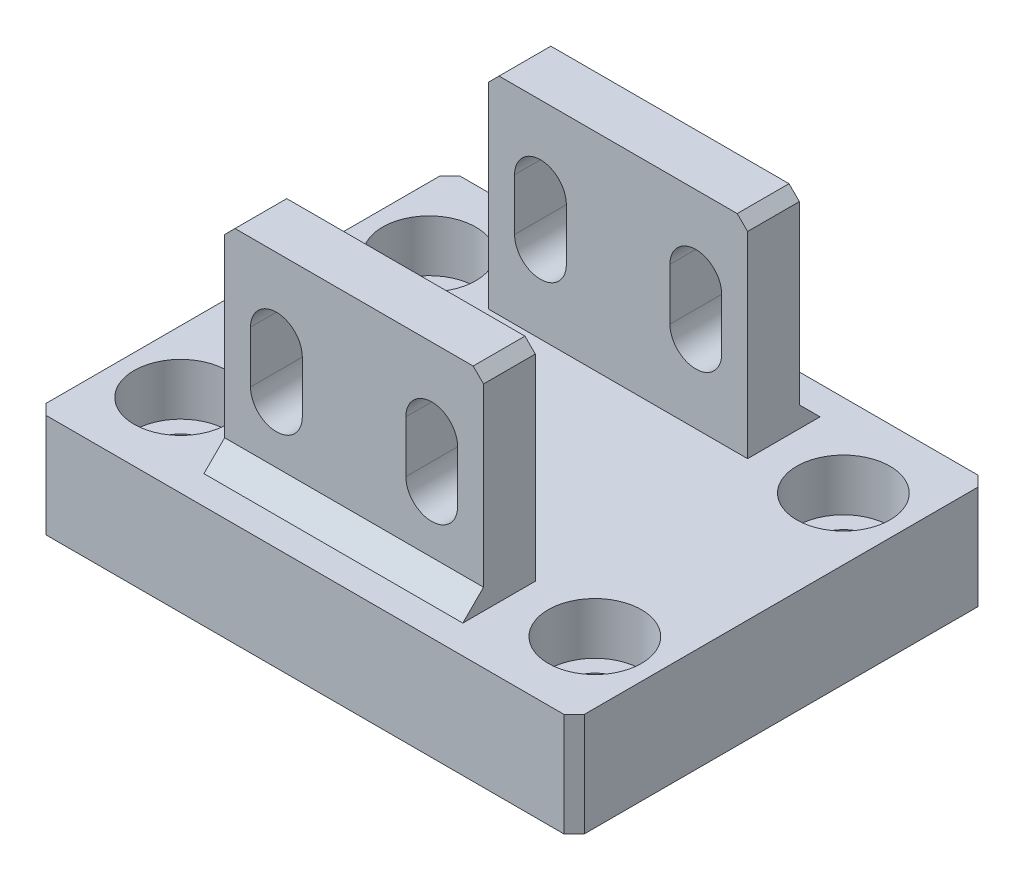
SolidWorks part; units mm, degrees
ref_plane "Front Plane" through (0, 0, 0) normal (0, 0, 1) x (1, 0, 0)
ref_plane "Top Plane" through (0, 0, 0) normal (0, 1, 0) x (1, 0, 0)
ref_plane "Right Plane" through (0, 0, 0) normal (1, 0, 0) x (0, 0, -1)
sketch "Sketch1" plane through (0, 0, 0) normal (0, 1, 0) x (1, 0, 0)
  line L1 (-26, 20) -> (26, 20)
  line L2 (-26, 20) -> (-26, -20)
  line L3 (-26, -20) -> (26, -20)
  line L4 (26, 20) -> (26, -20)
  line L5 (-26, 20) -> (26, -20) construction
  line L6 (-26, -20) -> (26, 20) construction
  line L7 (-20, 12) -> (20, 12) construction
  line L8 (-20, 12) -> (-20, -12) construction
  line L9 (-20, -12) -> (20, -12) construction
  line L10 (20, 12) -> (20, -12) construction
  line L11 (-20, 12) -> (20, -12) construction
  line L12 (-20, -12) -> (20, 12) construction
  circle A0 centre (-20, 12) radius 2.75
  circle A1 centre (20, 12) radius 2.75
  circle A2 centre (20, -12) radius 2.75
  circle A3 centre (-20, -12) radius 2.75
  point P0 (0, 0)
  point P6 (0, 0)
  dimension "D5" = 5.5
  dimension "D1" = 52
  dimension "D2" = 40
  dimension "D3" = 24
  dimension "D4" = 40
extrude "Boss-Extrude1" add sketch "Sketch1" along normal blind 10
sketch "Sketch4" plane through (0, 10, 0) normal (0, 1, 0) x (1, 0, 0)
  circle A0 centre (-20, 12) radius 4.5
  circle A1 centre (20, 12) radius 4.5
  circle A2 centre (20, -12) radius 4.5
  circle A3 centre (-20, -12) radius 4.5
  dimension "D1" = 9
extrude "Cut-Extrude2" cut sketch "Sketch4" against normal blind 5
sketch "Sketch2" plane through (26, 0, 0) normal (1, 0, 0) x (0, 0, -1)
  line L5 (0, -3.5148) -> (0, 6.6641) construction
  line L10 (-20, 10) -> (20, 10) construction
  line L11 (-15.25, 10) -> (-10.25, 10)
  line L12 (-15.25, 10) -> (-15.25, 30)
  line L13 (-15.25, 30) -> (-10.25, 30)
  line L14 (-10.25, 10) -> (-10.25, 30)
  line L16 (15.25, 10) -> (10.25, 10)
  line L17 (15.25, 10) -> (15.25, 30)
  line L18 (15.25, 30) -> (10.25, 30)
  line L19 (10.25, 10) -> (10.25, 30)
  dimension "D1" = 20.5
  dimension "D2" = 5
  dimension "D3" = 20
extrude "Boss-Extrude2" add sketch "Sketch2" against normal blind 25 from offset 13.5 offset against normal yes
sketch "Sketch3" plane through (0, 0, 15.25) normal (0, 0, 1) x (1, 0, 0)
  line L0 (-7.5, 22.5) -> (-7.5, 17.5) construction
  line L1 (-5, 22.5) -> (-5, 17.5)
  line L2 (-10, 22.5) -> (-10, 17.5)
  line L3 (7.5, 22.5) -> (7.5, 17.5) construction
  line L4 (10, 22.5) -> (10, 17.5)
  line L5 (5, 22.5) -> (5, 17.5)
  line L6 (-12.5, 30) -> (12.5, 30) construction
  line L7 (0, -4.8906) -> (0, 2.3795) construction
  arc A0 (-5, 22.5) -> (-10, 22.5) centre (-7.5, 22.5) ccw
  arc A1 (-10, 17.5) -> (-5, 17.5) centre (-7.5, 17.5) ccw
  arc A2 (10, 22.5) -> (5, 22.5) centre (7.5, 22.5) ccw
  arc A3 (5, 17.5) -> (10, 17.5) centre (7.5, 17.5) ccw
  point P2 (-7.5, 20)
  point P7 (7.5, 20)
  point P17 (-7.427, 12.5)
  dimension "D1" = 5
  dimension "D2" = 10
  dimension "D3" = 5
  dimension "D4" = 15
extrude "Cut-Extrude1" cut sketch "Sketch3" against normal up to surface (30.5 mm away) up to face at (0, 20, -15.25)
chamfer "Chamfer1" distance 2 angle 45 2 edges at (0, 10, -15.25) (0, 10, 15.25)
chamfer "Chamfer2" distance 1 angle 45 8 edges at (-26, 5, 20) (-26, 5, -20) (26, 5, -20) (26, 5, 20) (-12.5, 30, 12.75) (12.5, 30, 12.75) (12.5, 30, -12.75) (-12.5, 30, -12.75)
